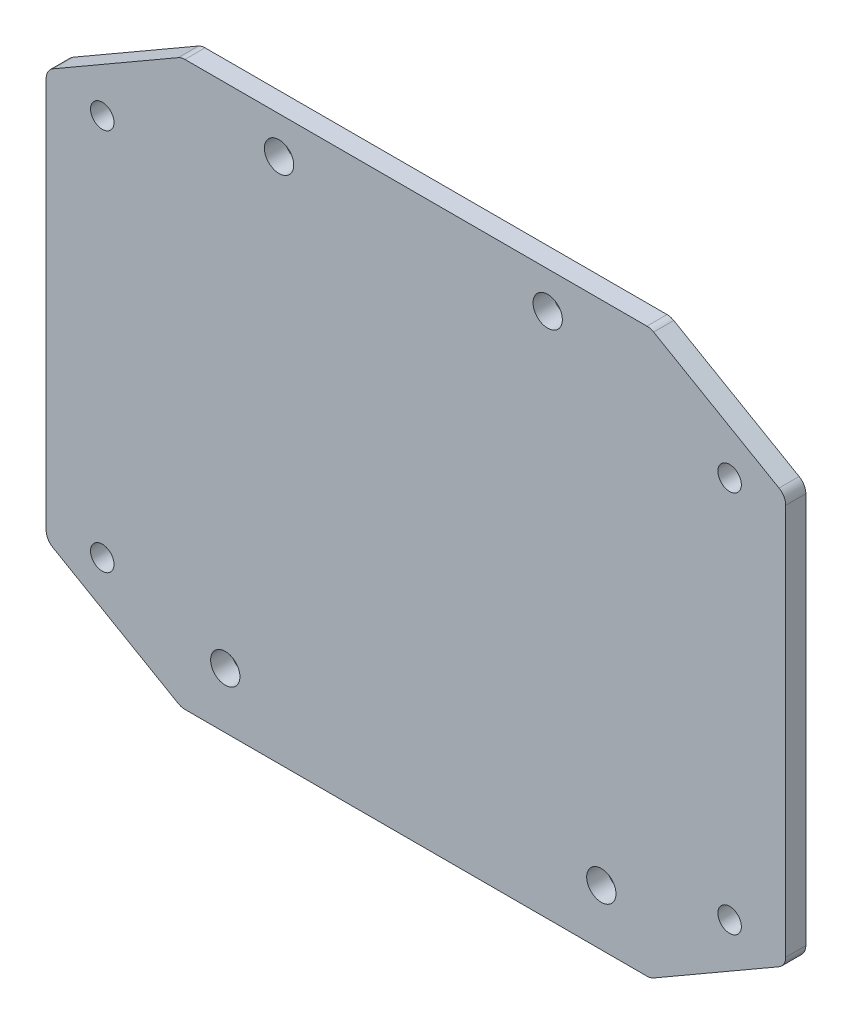
SolidWorks part; units mm, degrees
ref_plane "前视基准面" through (0, 0, 0) normal (0, 0, 1) x (1, 0, 0)
ref_plane "上视基准面" through (0, 0, 0) normal (0, 1, 0) x (1, 0, 0)
ref_plane "右视基准面" through (0, 0, 0) normal (1, 0, 0) x (0, 0, -1)
sketch "草图1" plane through (0, 0, 0) normal (0, 0, 1) x (1, 0, 0)
  line L0 (-35, 0) -> (35, 0) construction
  line L1 (-34.4641, 23.2874) -> (34.4641, 23.2874)
  line L2 (-34.4641, -23.2874) -> (34.4641, -23.2874)
  line L7 (35.4641, -23.0195) -> (54.1675, -12.2211)
  line L8 (55.1675, -10.489) -> (55.1675, 10.489)
  line L9 (54.1675, 12.2211) -> (35.4641, 23.0195)
  line L10 (-35.4641, 23.0195) -> (-54.1675, 12.2211)
  line L11 (-55.1675, 10.489) -> (-55.1675, -10.489)
  line L12 (-54.1675, -12.2211) -> (-35.4641, -23.0195)
  line L16 (-24.9163, 17.4656) -> (-35, 23.2874) [skipped]
  line L17 (-24.9163, -17.4656) -> (-14.8325, -11.6437) [skipped]
  line L18 (-14.8325, -11.6437) -> (-14.8325, 0) [skipped]
  line L19 (24.9163, -17.4656) -> (35, -23.2874) [skipped]
  line L20 (14.8325, 11.6437) -> (14.8325, 0) [skipped]
  line L21 (35, 23.2874) -> (24.9163, 17.4656) [skipped]
  arc A0 (-55.1675, -10.489) -> (-54.1675, -12.2211) centre (-53.1675, -10.489) ccw
  arc A1 (-54.1675, 12.2211) -> (-55.1675, 10.489) centre (-53.1675, 10.489) ccw
  arc A2 (45.0837, -17.4656) -> (45.0837, 17.4656) centre (35, 0) ccw construction
  arc A3 (-45.0837, 17.4656) -> (-45.0837, -17.4656) centre (-35, 0) ccw construction
  arc A4 (55.1675, 10.489) -> (54.1675, 12.2211) centre (53.1675, 10.489) ccw
  arc A5 (54.1675, -12.2211) -> (55.1675, -10.489) centre (53.1675, -10.489) ccw
  arc A6 (34.4641, -23.2874) -> (35.4641, -23.0195) centre (34.4641, -21.2874) ccw
  arc A7 (-34.4641, -23.2874) -> (-35.4641, -23.0195) centre (-34.4641, -21.2874) cw
  arc A8 (34.4641, 23.2874) -> (35.4641, 23.0195) centre (34.4641, 21.2874) cw
  arc A9 (-34.4641, 23.2874) -> (-35.4641, 23.0195) centre (-34.4641, 21.2874) ccw
  point P2 (0, 0)
  dimension "D2" = 2
  dimension "D1" = 70
extrude "凸台-拉伸1" add sketch "草图1" along normal blind 3
sketch "草图2" plane through (0, 0, 3) normal (0, 0, 1) x (1, 0, 0)
  line L0 (-55.1675, 15.5514) -> (-55.1675, 10.489)
  line L1 (55.1675, 15.5514) -> (55.1675, 10.489)
  line L8 (-54.1675, -12.2211) -> (-35.4641, -23.0195)
  line L9 (-34.4641, -23.2874) -> (34.4641, -23.2874)
  line L10 (35.4641, -23.0195) -> (54.1675, -12.2211)
  line L11 (55.1675, -10.489) -> (55.1675, 10.489)
  line L12 (54.1675, 12.2211) -> (35.4641, 23.0195)
  line L13 (34.4641, 23.2874) -> (-34.4641, 23.2874)
  line L14 (-35.4641, 23.0195) -> (-54.1675, 12.2211)
  line L15 (-55.1675, 10.489) -> (-55.1675, -10.489)
  line L16 (-54.1675, -12.2211) -> (-35.4641, -23.0195)
  line L17 (-34.4641, -23.2874) -> (34.4641, -23.2874)
  line L18 (35.4641, -23.0195) -> (54.1675, -12.2211)
  line L19 (55.1675, 15.5514) -> (55.1675, 36.5294)
  line L20 (54.1675, 38.2614) -> (35.4641, 49.0598)
  line L21 (34.4641, 49.3278) -> (-34.4641, 49.3278)
  line L22 (-35.4641, 49.0598) -> (-54.1675, 38.2614)
  line L23 (-55.1675, 36.5294) -> (-55.1675, 15.5514)
  line L24 (55.1675, -10.489) -> (55.1675, 10.489)
  line L28 (-55.1675, 10.489) -> (-55.1675, -10.489)
  arc A8 (-55.1675, -10.489) -> (-54.1675, -12.2211) centre (-53.1675, -10.489) ccw
  arc A9 (-35.4641, -23.0195) -> (-34.4641, -23.2874) centre (-34.4641, -21.2874) ccw
  arc A10 (34.4641, -23.2874) -> (35.4641, -23.0195) centre (34.4641, -21.2874) ccw
  arc A11 (54.1675, -12.2211) -> (55.1675, -10.489) centre (53.1675, -10.489) ccw
  arc A12 (55.1675, 10.489) -> (54.1675, 12.2211) centre (53.1675, 10.489) ccw
  arc A13 (35.4641, 23.0195) -> (34.4641, 23.2874) centre (34.4641, 21.2874) ccw
  arc A14 (-34.4641, 23.2874) -> (-35.4641, 23.0195) centre (-34.4641, 21.2874) ccw
  arc A15 (-54.1675, 12.2211) -> (-55.1675, 10.489) centre (-53.1675, 10.489) ccw
  arc A17 (-55.1675, -10.489) -> (-54.1675, -12.2211) centre (-53.1675, -10.489) ccw
  arc A18 (-35.4641, -23.0195) -> (-34.4641, -23.2874) centre (-34.4641, -21.2874) ccw
  arc A20 (55.1675, 36.5294) -> (54.1675, 38.2614) centre (53.1675, 36.5294) ccw
  arc A21 (35.4641, 49.0598) -> (34.4641, 49.3278) centre (34.4641, 47.3278) ccw
  arc A22 (-34.4641, 49.3278) -> (-35.4641, 49.0598) centre (-34.4641, 47.3278) ccw
  arc A23 (-54.1675, 38.2614) -> (-55.1675, 36.5294) centre (-53.1675, 36.5294) ccw
  arc A24 (34.4641, -23.2874) -> (35.4641, -23.0195) centre (34.4641, -21.2874) ccw
  arc A25 (54.1675, -12.2211) -> (55.1675, -10.489) centre (53.1675, -10.489) ccw
  dimension "D1" = 0
extrude "凸台-拉伸2" add sketch "草图2" against normal up to surface (3 mm away) up to face at (0, 0, 0)
sketch "草图3" plane through (0, 0, 3) normal (0, 0, 1) x (1, 0, 0)
  line L0 (55.1675, 33.1863) -> (-55.1675, 33.1863)
  line L19 (55.1675, 33.1863) -> (55.1675, 47.9026)
  line L20 (54.1675, 49.6346) -> (35.4641, 60.433)
  line L21 (34.4641, 60.701) -> (-34.4641, 60.701)
  line L22 (-35.4641, 60.433) -> (-54.1675, 49.6346)
  line L23 (-55.1675, 47.9026) -> (-55.1675, 33.1863)
  arc A20 (55.1675, 47.9026) -> (54.1675, 49.6346) centre (53.1675, 47.9026) ccw
  arc A21 (35.4641, 60.433) -> (34.4641, 60.701) centre (34.4641, 58.701) ccw
  arc A22 (-34.4641, 60.701) -> (-35.4641, 60.433) centre (-34.4641, 58.701) ccw
  arc A23 (-54.1675, 49.6346) -> (-55.1675, 47.9026) centre (-53.1675, 47.9026) ccw
extrude "凸台-拉伸3" add sketch "草图3" against normal up to surface (3 mm away) up to face at (0, 13.0202, 0)
sketch "草图4" plane through (0, 0, 3) normal (0, 0, 1) x (1, 0, 0)
  circle A0 centre (-20.4246, 55.1619) radius 2.1871
  circle A1 centre (19.6555, 55.2218) radius 2.1871
  circle A2 centre (27.6587, -14.9599) radius 2.1871
  circle A3 centre (-28.4477, -14.9599) radius 2.1871
extrude "切除-拉伸1" cut sketch "草图4" against normal blind 10
sketch "草图5" plane through (0, 0, 3) normal (0, 0, 1) x (1, 0, 0)
  line L0 (0, 43.8874) -> (0, -15.3938) construction
  line L1 (-55.1675, 18.7068) -> (-43.0214, 18.7068) construction
  line L2 (-55.1675, 47.9026) -> (-55.1675, -10.489) construction
  circle A0 centre (46.7986, 47.2556) radius 1.75
  circle A1 centre (-46.7986, 47.2556) radius 1.75
  circle A2 centre (46.7986, -9.842) radius 1.75
  circle A3 centre (-46.7986, -9.842) radius 1.75
  dimension "D1" = 3.5
extrude "切除-拉伸2" cut sketch "草图5" against normal blind 10
